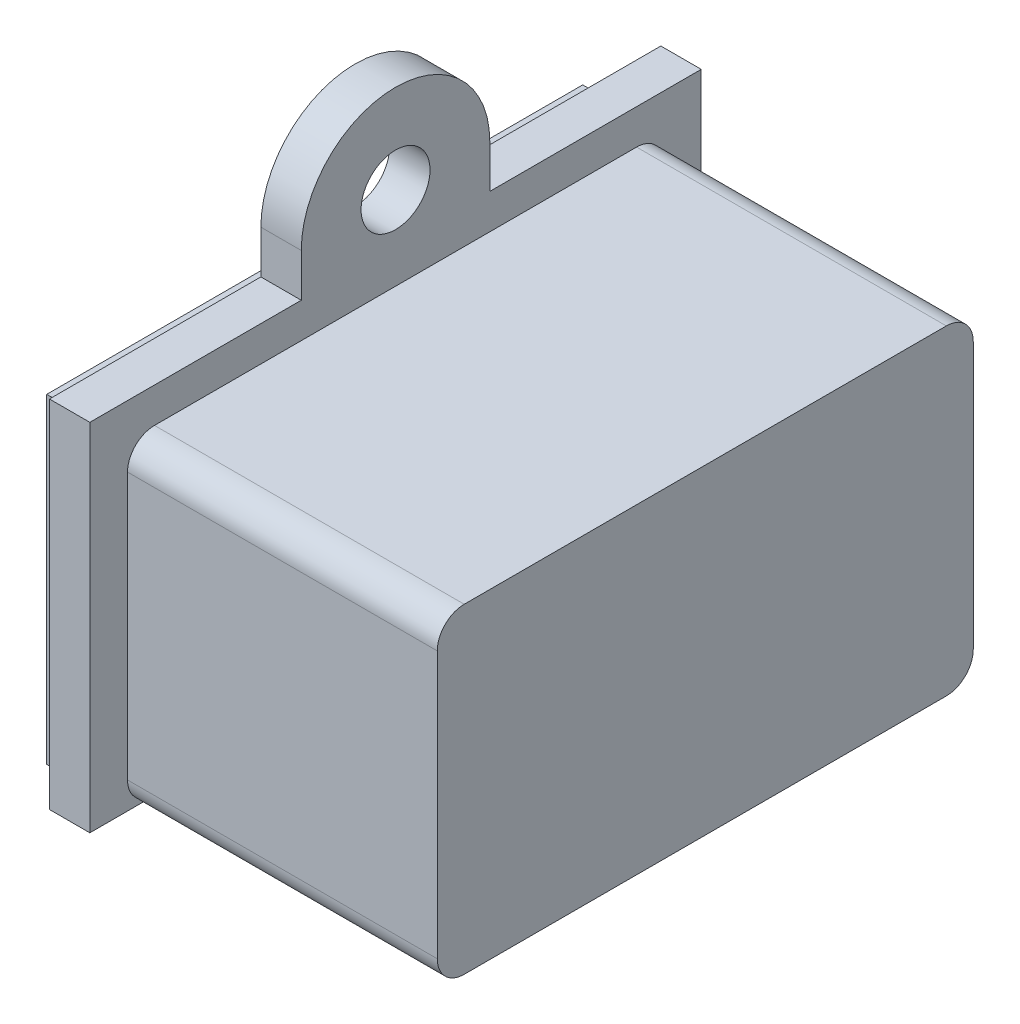
SolidWorks part; units mm, degrees
ref_plane "前视基准面" through (0, 0, 0) normal (0, 0, 1) x (1, 0, 0)
ref_plane "上视基准面" through (0, 0, 0) normal (0, 1, 0) x (1, 0, 0)
ref_plane "右视基准面" through (0, 0, 0) normal (1, 0, 0) x (0, 0, -1)
sketch "草图1" plane through (0, 0, 0) normal (1, 0, 0) x (0, 0, -1)
  line L0 (-3.857, 9.7346) -> (3.993, 9.7346)
  line L1 (-18.707, 9.7346) -> (-10.857, 9.7346)
  line L2 (-18.707, 9.7346) -> (-18.707, -3.4654)
  line L3 (-18.707, -3.4654) -> (3.993, -3.4654)
  line L4 (3.993, 9.7346) -> (3.993, -3.4654)
  line L5 (-3.857, 11.3346) -> (-3.857, 9.7346)
  line L7 (-10.857, 9.7346) -> (-10.857, 11.3346)
  line L9 (2.1591, 8.1286) -> (-17.1595, 8.1286)
  line L10 (2.1591, 8.1286) -> (2.1591, -1.9246)
  line L11 (2.1591, -1.9246) -> (-17.1595, -1.9246)
  line L12 (-17.1595, 8.1286) -> (-17.1595, -1.9246)
  circle A1 centre (-7.357, 11.5346) radius 1.28
  arc A3 (-10.857, 11.3346) -> (-3.857, 11.3346) centre (-7.357, 11.3346) cw
  point P8 (-7.357, 14.8346)
  dimension "D3" = 1.8
  dimension "D4" = 18.3
  dimension "D1" = 13.2
  dimension "D2" = 22.7
extrude "凸台-拉伸1" add sketch "草图1" along normal blind 1.5
sketch "草图2" plane through (0, 0, 0) normal (-1, 0, 0) x (0, 0, 1)
  line L8 (2.007, 6.7346) -> (12.707, 6.7346)
  line L9 (18.707, -3.4654) -> (-3.993, -3.4654) construction
  line L10 (-0.993, 3.7346) -> (-0.993, 1.2346)
  line L11 (2.007, -1.7654) -> (12.707, -1.7654)
  line L15 (17.307, -3.4654) -> (17.307, 8.4346)
  line L16 (17.307, 8.4346) -> (-2.593, 8.4346)
  line L17 (-2.593, -3.4654) -> (17.307, -3.4654)
  line L18 (-2.593, 8.4346) -> (-2.593, -3.4654)
  line L19 (-3.993, -3.4654) -> (-3.993, 9.7346) construction
  line L20 (15.707, 3.7346) -> (15.707, 1.2346)
  arc A13 (12.707, 6.7346) -> (15.707, 3.7346) centre (12.707, 3.7346) cw
  arc A14 (12.707, -1.7654) -> (15.707, 1.2346) centre (12.707, 1.2346) ccw
  arc A15 (-0.993, 1.2346) -> (2.007, -1.7654) centre (2.007, 1.2346) ccw
  arc A16 (2.007, 6.7346) -> (-0.993, 3.7346) centre (2.007, 3.7346) ccw
  point P12 (15.707, -1.7654)
  point P15 (-0.993, -1.7654)
  point P18 (-0.993, 6.7346)
  dimension "D4" = 1.4
  dimension "D10" = 3
  dimension "D1" = 19.9
  dimension "D2" = 11.9
  dimension "D3" = 0
  dimension "D5" = 11.9
  dimension "D6" = 16.7
  dimension "D7" = 8.5
  dimension "D8" = 1.7
  dimension "D9" = 1.6
extrude "凸台-拉伸2" add sketch "草图2" along normal blind 1.5 and the other way blind 12
sketch "草图3" plane through (-1.5, 0, 0) normal (-1, 0, 0) x (0, 0, 1)
  line L1 (12.707, 6.7346) -> (2.007, 6.7346) construction
  line L4 (12.707, 6.7346) -> (2.007, 6.7346) construction
  line L5 (8.557, 6.7346) -> (7.5285, 5.0205)
  line L6 (7.1855, 5.0205) -> (6.157, 6.7346)
  line L8 (2.007, -1.7654) -> (12.707, -1.7654) construction
  line L11 (2.007, -1.7654) -> (12.707, -1.7654) construction
  line L12 (6.157, -1.7654) -> (7.1855, -0.0512)
  line L13 (8.557, -1.7654) -> (7.5285, -0.0512)
  line L14 (-0.993, 3.7346) -> (-0.993, 1.2346) construction
  line L15 (15.707, 1.2346) -> (15.707, 3.7346) construction
  line L16 (6.157, 6.7346) -> (8.557, 6.7346)
  line L17 (6.157, -1.7654) -> (8.557, -1.7654)
  arc A2 (7.1855, 5.0205) -> (7.5285, 5.0205) centre (7.357, 5.1234) ccw
  arc A5 (7.5285, -0.0512) -> (7.1855, -0.0512) centre (7.357, -0.1541) ccw
  circle A6 centre (2.007, 2.4846) radius 1
  circle A7 centre (12.707, 2.4846) radius 1
  point P10 (8.557, 6.7346)
  point P13 (6.157, 6.7346)
  point P26 (8.557, -1.7654)
  point P29 (6.157, -1.7654)
  dimension "D3" = 3
  dimension "D4" = 3
extrude "凸台-拉伸4" add sketch "草图3" against normal blind 13 separate body
sketch "草图10" plane through (12, 0, 0) normal (1, 0, 0) x (0, 0, -1)
  line L1 (-17.307, 8.4346) -> (2.593, 8.4346)
  line L2 (-17.307, 8.4346) -> (-17.307, -3.4654)
  line L3 (-17.307, -3.4654) -> (2.593, -3.4654)
  line L4 (2.593, 8.4346) -> (2.593, -3.4654)
extrude "凸台-拉伸6" add sketch "草图10" along normal blind 1
fillet "圆角2" radius 1 4 edges at (7.25, -3.4654, 17.307) (7.25, 8.4346, 17.307) (7.25, -3.4654, -2.593) (7.25, 8.4346, -2.593)
sketch "草图11" plane through (12, 0, 0) normal (-1, 0, 0) x (0, 0, 1)
  circle A0 centre (2.007, 2.4846) radius 1.5
  circle A1 centre (12.707, 2.4846) radius 1.5
extrude "凸台-拉伸7" add sketch "草图11" along normal blind 1
fillet "圆角3" radius 0.2 1 edges at (-1.5, 2.4846, 3.007)
fillet "圆角4" radius 0.2 1 edges at (-1.5, 2.4846, 13.707)
